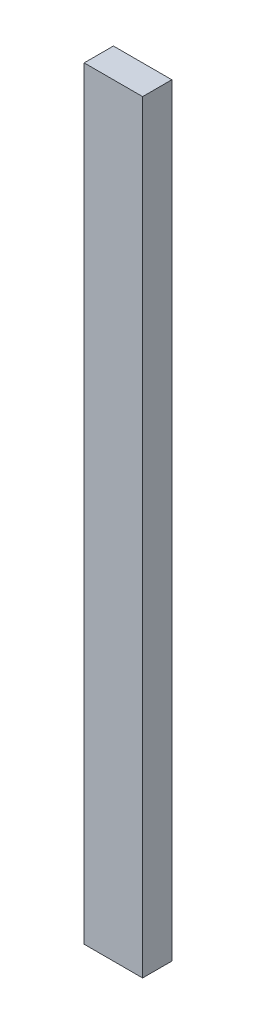
SolidWorks part; units mm, degrees
material "Sapin"
ref_plane "Plan de face" through (0, 0, 0) normal (0, 0, 1) x (1, 0, 0)
ref_plane "Plan de dessus" through (0, 0, 0) normal (0, 1, 0) x (1, 0, 0)
ref_plane "Plan de droite" through (0, 0, 0) normal (1, 0, 0) x (0, 0, -1)
sketch "Esquisse1" plane through (0, 0, 0) normal (0, 0, 1) x (1, 0, 0)
  line L1 (-24, -313.5) -> (24, -313.5)
  line L2 (-24, -313.5) -> (-24, 313.5)
  line L3 (-24, 313.5) -> (24, 313.5)
  line L4 (24, -313.5) -> (24, 313.5)
  line L5 (-24, -313.5) -> (24, 313.5) construction
  line L6 (-24, 313.5) -> (24, -313.5) construction
  point P0 (0, 0)
  dimension "D1" = 48
  dimension "D2" = 627
extrude "Boss.-Extru.1" add sketch "Esquisse1" along normal blind 24
